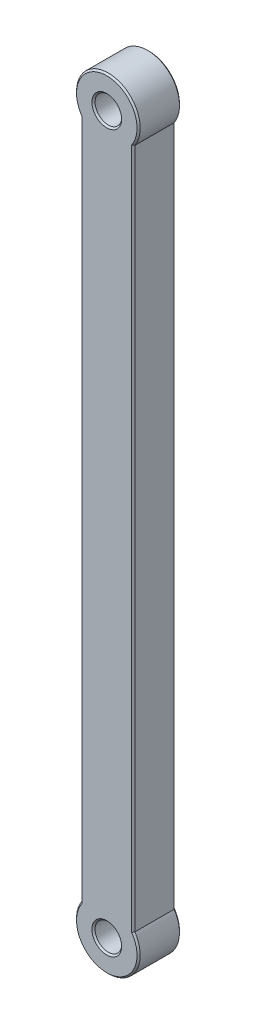
SolidWorks part; units mm, degrees
material "POM 乙缩醛共聚物"
ref_plane "前视基准面" through (0, 0, 0) normal (0, 0, 1) x (1, 0, 0)
ref_plane "上视基准面" through (0, 0, 0) normal (0, 1, 0) x (1, 0, 0)
ref_plane "右视基准面" through (0, 0, 0) normal (1, 0, 0) x (0, 0, -1)
sketch "草图1" plane through (0, 0, 0) normal (0, 0, 1) x (1, 0, 0)
  line L0 (0, 0) -> (0, 135) construction
  line L1 (-5, 0) -> (-5, 135)
  line L2 (5, 0) -> (5, 135)
  arc A0 (-5, 0) -> (5, 0) centre (0, 0) ccw
  arc A1 (5, 135) -> (-5, 135) centre (0, 135) ccw
  point P3 (0, 67.5)
  dimension "D1" = 135
  dimension "D2" = 10
extrude "凸台-拉伸1" add sketch "草图1" along normal blind 8
sketch "草图2" plane through (0, 0, 0) normal (0, 0, 1) x (1, 0, 0)
  circle A0 centre (0, 135) radius 6
  circle A1 centre (0, 0) radius 6
  dimension "D1" = 12
  dimension "D2" = 12
extrude "凸台-拉伸2" add sketch "草图2" along normal up to surface (8 mm away) up to face at (0, 67.5, 8)
sketch "草图3" plane through (0, 0, 0) normal (0, 0, -1) x (-1, 0, 0)
  circle A0 centre (0, 135) radius 2.5
  circle A1 centre (0, 0) radius 2.5
  dimension "D1" = 5
extrude "切除-拉伸1" cut sketch "草图3" against normal through all
chamfer "倒角1" distance 0.3 angle 45 12 edges at (0, 141, 8) (0, 141, 0) (-5, 67.5, 0) (0, -6, 0) (0, -6, 8) (5, 67.5, 0) (-2.5, 0, 0) (-2.5, 135, 0) (-5, 67.5, 8) (5, 67.5, 8) (-2.5, 0, 8) (-2.5, 135, 8)
